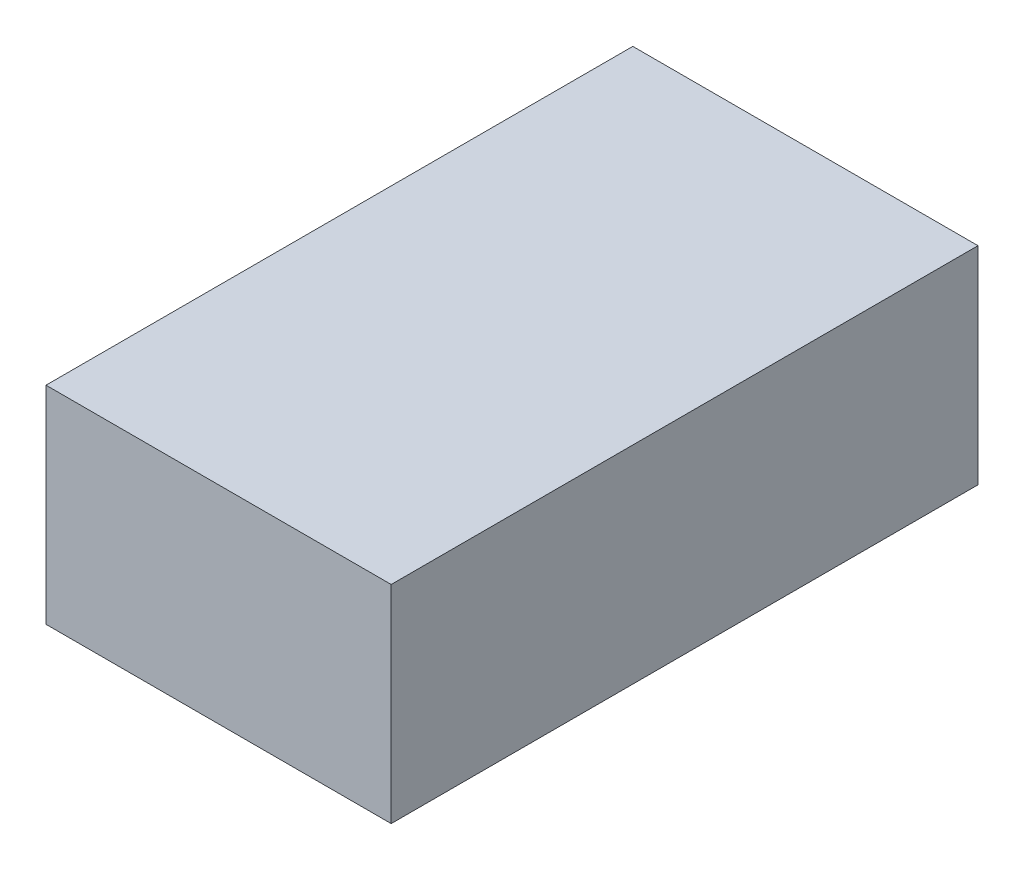
SolidWorks part; units mm, degrees
ref_plane "Plan de face" through (0, 0, 0) normal (0, 0, 1) x (1, 0, 0)
ref_plane "Plan de dessus" through (0, 0, 0) normal (0, 1, 0) x (1, 0, 0)
ref_plane "Plan de droite" through (0, 0, 0) normal (1, 0, 0) x (0, 0, -1)
sketch "Esquisse1" plane through (0, 0, 0) normal (0, 1, 0) x (1, 0, 0)
  line L1 (0, -42.5) -> (50, -42.5)
  line L2 (0, -42.5) -> (0, 42.5)
  line L3 (0, 42.5) -> (50, 42.5)
  line L4 (50, -42.5) -> (50, 42.5)
  dimension "D1" = 85
  dimension "D2" = 50
extrude "Boss.-Extru.1" add sketch "Esquisse1" along normal blind 30
